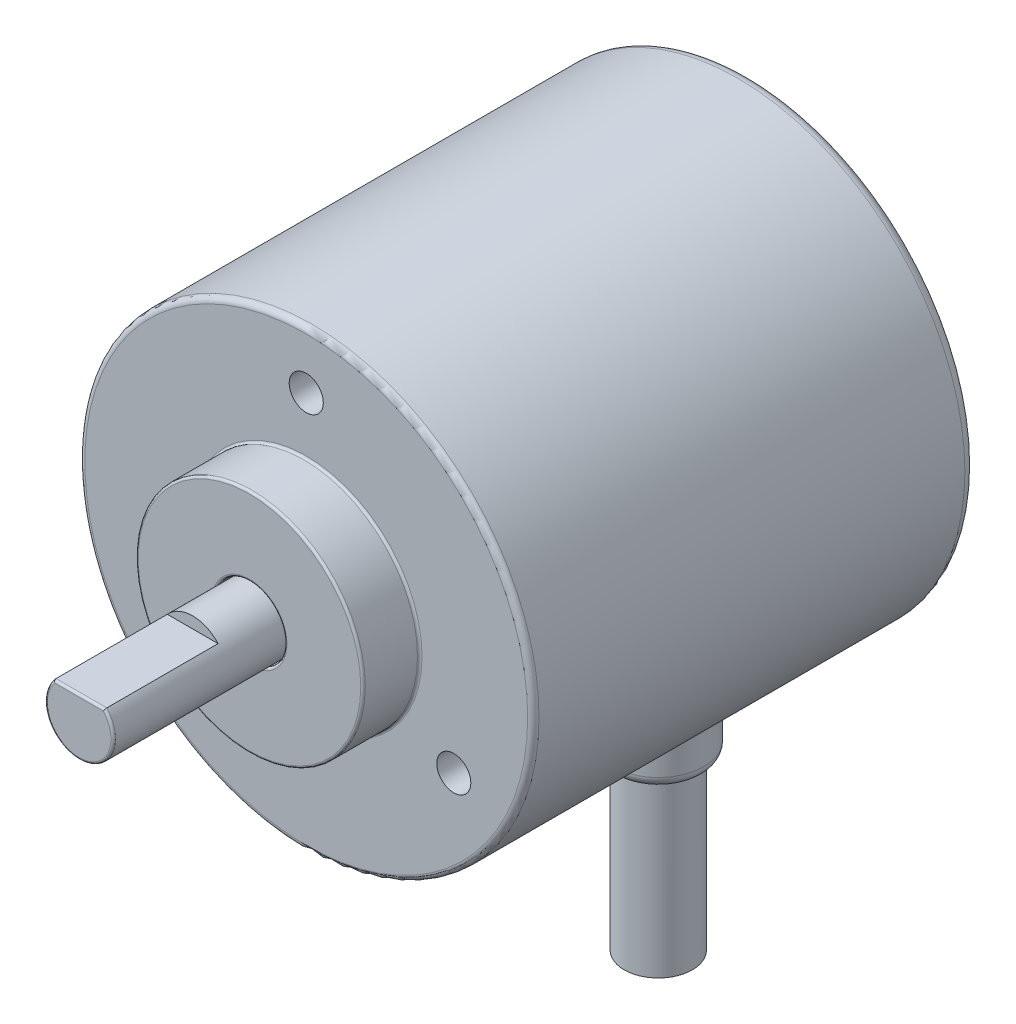
SolidWorks part; units mm, degrees
ref_plane "前视基准面" through (0, 0, 0) normal (0, 0, 1) x (1, 0, 0)
ref_plane "上视基准面" through (0, 0, 0) normal (0, 1, 0) x (1, 0, 0)
ref_plane "右视基准面" through (0, 0, 0) normal (1, 0, 0) x (0, 0, -1)
sketch "Sketch1" plane through (0, 0, 0) normal (0, 0, 1) x (1, 0, 0)
  circle A0 centre (0, 0) radius 20
  dimension "D1" = 40
extrude "Boss-Extrude1" add sketch "Sketch1" along normal blind 39
sketch "Sketch2" plane through (0, 0, 39) normal (0, 0, 1) x (1, 0, 0)
  circle A0 centre (0, 0) radius 10
  dimension "D1" = 20
extrude "Boss-Extrude2" add sketch "Sketch2" along normal blind 5
sketch "Sketch3" plane through (0, 0, 44) normal (0, 0, 1) x (1, 0, 0)
  circle A0 centre (0, 0) radius 3
  dimension "D1" = 6
extrude "Boss-Extrude3" add sketch "Sketch3" along normal blind 15
sketch "Sketch4" plane through (0, 0, 59) normal (0, 0, 1) x (1, 0, 0)
  line L0 (-2.2361, 2) -> (2.2361, 2)
  circle A0 centre (0, 0) radius 3 construction
  arc A1 (2.2361, 2) -> (-2.2361, 2) centre (0, 0) ccw
  dimension "D1" = 2
extrude "Cut-Extrude1" cut sketch "Sketch4" against normal blind 10
sketch "Sketch5" plane through (0, 0, 39) normal (0, 0, 1) x (1, 0, 0)
  circle A0 centre (0, 0) radius 15 construction
  circle A1 centre (0, 15) radius 1.5
  circle A2 centre (12.9904, -7.5) radius 1.5
  circle A3 centre (-12.9904, -7.5) radius 1.5
  point P11 (0, 0)
  dimension "D1" = 30
  dimension "D2" = 3
extrude "Cut-Extrude2" cut sketch "Sketch5" against normal blind 7
sketch "Sketch6" plane through (0, 0, 0) normal (0, 1, 0) x (1, 0, 0)
  circle A0 centre (0, -8) radius 4
  dimension "D1" = 8
  dimension "D2" = 8
extrude "Boss-Extrude4" add sketch "Sketch6" against normal blind 28
fillet "Fillet1" radius 0.5 1 edges at (20, 0, 39)
fillet "Fillet2" radius 1 1 edges at (20, 0, 0)
fillet "Fillet3" radius 1 1 edges at (0, -28, 12)
sketch "Sketch7" plane through (0, -28, 0) normal (0, -1, 0) x (1, 0, 0)
  circle A0 centre (0, 8) radius 3
extrude "Boss-Extrude5" add sketch "Sketch7" along normal blind 15
fillet "Fillet4" radius 0.2 1 edges at (10, 0, 44)
fillet "Fillet5" radius 0.2 2 edges at (0, 2, 59) (0, -3, 59)
sketch "Sketch8" plane through (0, 0, 44) normal (0, 0, 1) x (1, 0, 0)
  circle A1 centre (0, 0) radius 3
  circle A2 centre (0, 0) radius 3.1
  circle A3 centre (0, 0) radius 3.1
  dimension "D1" = 0.1
extrude "Cut-Extrude3" cut sketch "Sketch8" against normal blind 5
fillet "Fillet6" radius 0.2 1 edges at (10, 0, 39)
fillet "Fillet7" radius 0.2 1 edges at (3.1, 0, 44)
